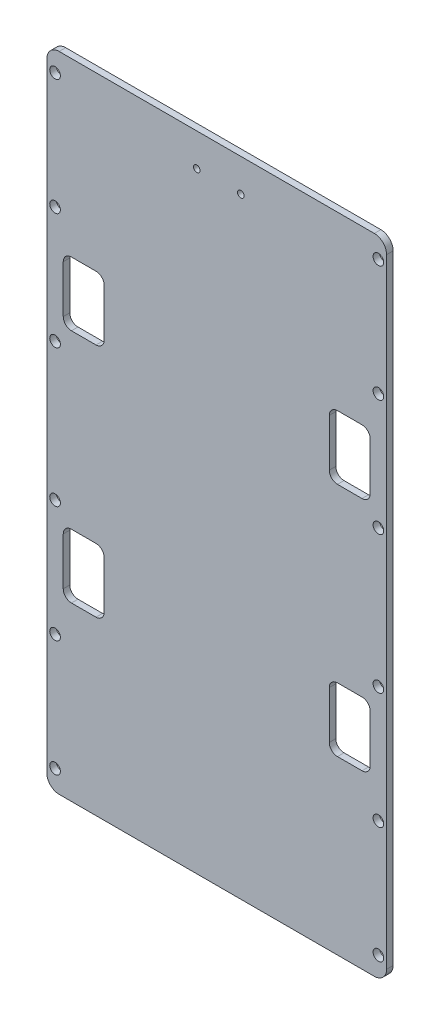
SolidWorks part; units mm, degrees
material "FR4_stuffedProtoboard"
ref_plane "Front Plane" through (0, 0, 0) normal (0, 0, 1) x (1, 0, 0)
ref_plane "Top Plane" through (0, 0, 0) normal (0, 1, 0) x (1, 0, 0)
ref_plane "Right Plane" through (0, 0, 0) normal (1, 0, 0) x (0, 0, -1)
sketch "Sketch1" plane through (0, 0, 0) normal (0, 0, 1) x (1, 0, 0)
  line L0 (-41.5, 0) -> (0, 0) construction
  line L1 (-38.5, 78.6) -> (38.5, 78.6)
  line L2 (-41.5, 75.6) -> (-41.5, -75.6)
  line L3 (-38.5, -78.6) -> (38.5, -78.6)
  line L4 (41.5, 75.6) -> (41.5, -75.6)
  line L5 (0, 0) -> (41.5, 0) construction
  line L7 (-34.5, 74.6) -> (-20.5, 74.6)
  line L8 (-37.5, 71.6) -> (-37.5, 52.1)
  line L9 (-35, 49.6) -> (-20.5, 49.6)
  line L10 (-17.5, 71.6) -> (-17.5, 52.6)
  line L11 (-12, 74.6) -> (13, 74.6)
  line L12 (-14.5, 72.1) -> (-14.5, 52.1)
  line L13 (-12, 49.6) -> (13, 49.6)
  line L14 (15.5, 72.1) -> (15.5, 52.1)
  line L15 (21, 74.6) -> (35, 74.6)
  line L16 (18.5, 72.1) -> (18.5, 52.1)
  line L17 (21, 49.6) -> (35, 49.6)
  line L18 (37.5, 72.1) -> (37.5, 52.1)
  line L19 (-35, 46.6) -> (-20, 46.6)
  line L20 (-37.5, 44.1) -> (-37.5, 21.1)
  line L21 (-35, 18.6) -> (-20, 18.6)
  line L22 (-17.5, 44.1) -> (-17.5, 21.1)
  line L23 (-12, 46.6) -> (13, 46.6)
  line L24 (-14.5, 44.1) -> (-14.5, 21.1)
  line L25 (-12, 18.6) -> (13, 18.6)
  line L26 (15.5, 44.1) -> (15.5, 21.1)
  line L27 (21, 46.6) -> (35, 46.6)
  line L28 (18.5, 44.1) -> (18.5, 21.1)
  line L29 (21, 18.6) -> (35, 18.6)
  line L30 (37.5, 44.1) -> (37.5, 21.1)
  line L31 (-35, 15.6) -> (-20, 15.6)
  line L32 (-37.5, 13.1) -> (-37.5, -13.1)
  line L33 (-35, -15.6) -> (-20, -15.6)
  line L34 (-17.5, 13.1) -> (-17.5, -13.1)
  line L35 (-12, 15.6) -> (13, 15.6)
  line L36 (-14.5, 13.1) -> (-14.5, -13.1)
  line L37 (-12, -15.6) -> (13, -15.6)
  line L38 (15.5, 13.1) -> (15.5, -13.1)
  line L39 (21, 15.6) -> (35, 15.6)
  line L40 (18.5, 13.1) -> (18.5, -13.1)
  line L41 (21, -15.6) -> (35, -15.6)
  line L42 (37.5, 13.1) -> (37.5, -13.1)
  line L43 (-35, -18.6) -> (-20, -18.6)
  line L44 (-37.5, -21.1) -> (-37.5, -44.1)
  line L45 (-35, -46.6) -> (-20, -46.6)
  line L46 (-17.5, -21.1) -> (-17.5, -44.1)
  line L47 (-12, -18.6) -> (13, -18.6)
  line L48 (-14.5, -21.1) -> (-14.5, -44.1)
  line L49 (-12, -46.6) -> (13, -46.6)
  line L50 (15.5, -21.1) -> (15.5, -44.1)
  line L51 (21, -18.6) -> (35, -18.6)
  line L52 (18.5, -21.1) -> (18.5, -44.1)
  line L53 (21, -46.6) -> (35, -46.6)
  line L54 (37.5, -21.1) -> (37.5, -44.1)
  line L55 (-35, -49.6) -> (-20, -49.6)
  line L56 (-37.5, -52.1) -> (-37.5, -72.1)
  line L57 (-35, -74.6) -> (-20, -74.6)
  line L58 (-17.5, -52.1) -> (-17.5, -72.1)
  line L59 (-12, -49.6) -> (13, -49.6)
  line L60 (-14.5, -52.1) -> (-14.5, -72.1)
  line L61 (-12, -74.6) -> (13, -74.6)
  line L62 (15.5, -52.1) -> (15.5, -72.1)
  line L63 (21, -49.6) -> (35, -49.6)
  line L64 (18.5, -52.1) -> (18.5, -72.1)
  line L65 (21, -74.6) -> (35, -74.6)
  line L66 (37.5, -52.1) -> (37.5, -72.1)
  arc A0 (-41.5, -75.6) -> (-38.5, -78.6) centre (-38.5, -75.6) ccw
  arc A1 (38.5, -78.6) -> (41.5, -75.6) centre (38.5, -75.6) ccw
  arc A2 (38.5, 78.6) -> (41.5, 75.6) centre (38.5, 75.6) cw
  arc A3 (-38.5, 78.6) -> (-41.5, 75.6) centre (-38.5, 75.6) ccw
  arc A4 (-20.5, 49.6) -> (-17.5, 52.6) centre (-20.5, 52.6) ccw
  arc A5 (-20.5, 74.6) -> (-17.5, 71.6) centre (-20.5, 71.6) cw
  arc A6 (-34.5, 74.6) -> (-37.5, 71.6) centre (-34.5, 71.6) ccw
  arc A7 (-20, -18.6) -> (-17.5, -21.1) centre (-20, -21.1) cw
  arc A8 (-35, -18.6) -> (-37.5, -21.1) centre (-35, -21.1) ccw
  arc A9 (-37.5, -44.1) -> (-35, -46.6) centre (-35, -44.1) ccw
  arc A10 (-20, -46.6) -> (-17.5, -44.1) centre (-20, -44.1) ccw
  arc A11 (-14.5, -44.1) -> (-12, -46.6) centre (-12, -44.1) ccw
  arc A12 (-12, -18.6) -> (-14.5, -21.1) centre (-12, -21.1) ccw
  arc A13 (13, -18.6) -> (15.5, -21.1) centre (13, -21.1) cw
  arc A14 (13, -46.6) -> (15.5, -44.1) centre (13, -44.1) ccw
  arc A15 (18.5, -44.1) -> (21, -46.6) centre (21, -44.1) ccw
  arc A16 (21, -18.6) -> (18.5, -21.1) centre (21, -21.1) ccw
  arc A17 (35, -18.6) -> (37.5, -21.1) centre (35, -21.1) cw
  arc A18 (35, -46.6) -> (37.5, -44.1) centre (35, -44.1) ccw
  arc A19 (35, -49.6) -> (37.5, -52.1) centre (35, -52.1) cw
  arc A20 (35, -74.6) -> (37.5, -72.1) centre (35, -72.1) ccw
  arc A21 (18.5, -72.1) -> (21, -74.6) centre (21, -72.1) ccw
  arc A22 (21, -49.6) -> (18.5, -52.1) centre (21, -52.1) ccw
  arc A23 (13, -49.6) -> (15.5, -52.1) centre (13, -52.1) cw
  arc A24 (13, -74.6) -> (15.5, -72.1) centre (13, -72.1) ccw
  arc A25 (-14.5, -72.1) -> (-12, -74.6) centre (-12, -72.1) ccw
  arc A26 (-12, -49.6) -> (-14.5, -52.1) centre (-12, -52.1) ccw
  arc A27 (-20, -49.6) -> (-17.5, -52.1) centre (-20, -52.1) cw
  arc A28 (-35, -49.6) -> (-37.5, -52.1) centre (-35, -52.1) ccw
  arc A29 (-37.5, -72.1) -> (-35, -74.6) centre (-35, -72.1) ccw
  arc A30 (-20, -74.6) -> (-17.5, -72.1) centre (-20, -72.1) ccw
  arc A31 (-37.5, -13.1) -> (-35, -15.6) centre (-35, -13.1) ccw
  arc A32 (-35, 15.6) -> (-37.5, 13.1) centre (-35, 13.1) ccw
  arc A33 (-20, 15.6) -> (-17.5, 13.1) centre (-20, 13.1) cw
  arc A34 (-20, -15.6) -> (-17.5, -13.1) centre (-20, -13.1) ccw
  arc A35 (-14.5, -13.1) -> (-12, -15.6) centre (-12, -13.1) ccw
  arc A36 (-12, 15.6) -> (-14.5, 13.1) centre (-12, 13.1) ccw
  arc A37 (13, 15.6) -> (15.5, 13.1) centre (13, 13.1) cw
  arc A38 (13, -15.6) -> (15.5, -13.1) centre (13, -13.1) ccw
  arc A39 (18.5, -13.1) -> (21, -15.6) centre (21, -13.1) ccw
  arc A40 (35, -15.6) -> (37.5, -13.1) centre (35, -13.1) ccw
  arc A41 (21, 15.6) -> (18.5, 13.1) centre (21, 13.1) ccw
  arc A42 (35, 15.6) -> (37.5, 13.1) centre (35, 13.1) cw
  arc A43 (35, 18.6) -> (37.5, 21.1) centre (35, 21.1) ccw
  arc A44 (18.5, 21.1) -> (21, 18.6) centre (21, 21.1) ccw
  arc A45 (21, 46.6) -> (18.5, 44.1) centre (21, 44.1) ccw
  arc A46 (35, 46.6) -> (37.5, 44.1) centre (35, 44.1) cw
  arc A47 (35, 49.6) -> (37.5, 52.1) centre (35, 52.1) ccw
  arc A48 (35, 74.6) -> (37.5, 72.1) centre (35, 72.1) cw
  arc A49 (18.5, 52.1) -> (21, 49.6) centre (21, 52.1) ccw
  arc A50 (21, 74.6) -> (18.5, 72.1) centre (21, 72.1) ccw
  arc A51 (13, 49.6) -> (15.5, 52.1) centre (13, 52.1) ccw
  arc A52 (13, 74.6) -> (15.5, 72.1) centre (13, 72.1) cw
  arc A53 (-12, 74.6) -> (-14.5, 72.1) centre (-12, 72.1) ccw
  arc A54 (-14.5, 52.1) -> (-12, 49.6) centre (-12, 52.1) ccw
  arc A55 (13, 18.6) -> (15.5, 21.1) centre (13, 21.1) ccw
  arc A56 (13, 46.6) -> (15.5, 44.1) centre (13, 44.1) cw
  arc A57 (-12, 46.6) -> (-14.5, 44.1) centre (-12, 44.1) ccw
  arc A58 (-14.5, 21.1) -> (-12, 18.6) centre (-12, 21.1) ccw
  arc A59 (-37.5, 21.1) -> (-35, 18.6) centre (-35, 21.1) ccw
  arc A60 (-20, 18.6) -> (-17.5, 21.1) centre (-20, 21.1) ccw
  arc A61 (-20, 46.6) -> (-17.5, 44.1) centre (-20, 44.1) cw
  arc A62 (-35, 46.6) -> (-37.5, 44.1) centre (-35, 44.1) ccw
  arc A63 (-37.5, 52.1) -> (-35, 49.6) centre (-35, 52.1) ccw
  point P72 (41.5, -78.6)
  point P75 (41.5, 78.6)
  point P78 (-41.5, 78.6)
  point P159 (37.5, 18.6)
  point P166 (37.5, 46.6)
  point P169 (37.5, 49.6)
  point P172 (37.5, 74.6)
  point P181 (15.5, 74.6)
  point P184 (-14.5, 74.6)
  dimension "D16" = 3
  dimension "D17" = 3
  dimension "D18" = 2.5
  dimension "D1" = 3
  dimension "D2" = 3
  dimension "D3" = 3
  dimension "D4" = 3
  dimension "D5" = 3
  dimension "D6" = 3
  dimension "D7" = 4
  dimension "D8" = 4
  dimension "D9" = 4
  dimension "D10" = 4
  dimension "D11" = 157.2
  dimension "D12" = 83
  dimension "D13" = 30
  dimension "D14" = 25
  dimension "D15" = 28
extrude "General Shape" add sketch "Sketch1" along normal blind 1.6 contours L8 A63 L9 A4 L10 A5 L7 A6 | L12 A54 L13 A51 L14 A52 L11 A53 | L15 A50 L16 A49 L17 A47 L18 A48 | L1 A3 L2 A0 L3 A1 L4 A2 A63 L8 A6 L7 A5 L10 A4 L9 A62 L19 A61 L22 A60 L21 A59 L20 A58 L24 A57 L23 A56 L26 A55 L25 A54 L12 A53 L11 A52 L14 A51 L13 A50 L15 A48 L18 A47 L17 | L24 A58 L25 A55 L26 A56 L23 A57 | L19 A62 L20 A59 L21 A60 L22 A61 | A46 L27 A45 L28 A44 L29 A43 L30 | A42 L39 A41 L40 A39 L41 A40 L42 | L37 A38 L38 A37 L35 A36 L36 A35 | L33 A34 L34 A33 L31 A32 L32 A31 | L45 A10 L46 A7 L43 A8 L44 A9 | L49 A14 L50 A13 L47 A12 L48 A11 | L53 A18 L54 A17 L51 A16 L52 A15 | L63 A22 L64 A21 L65 A20 L66 A19 | L59 A26 L60 A25 L61 A24 L62 A23 | L57 A30 L58 A27 L55 A28 L56 A29
sketch "Sketch2" plane through (0, 0, 0) normal (0, 0, -1) x (-1, 0, 0)
  line L0 (38.5, 78.6) -> (-38.5, 78.6) construction
  line L1 (-22, 64) -> (0, 64) construction
  line L2 (-41.5, 75.6) -> (-41.5, -75.6) construction
  line L3 (-22, 64) -> (-22, 54) construction
  line L4 (-22, -71.6) -> (0, -71.6) construction
  line L5 (-22, -71.6) -> (-22, -61.6) construction
  line L7 (38.5, -78.6) -> (-38.5, -78.6) construction
  line L8 (-41.5, 75.6) -> (-41.5, -75.6) construction
  circle A0 centre (-22, 64) radius 1.2
  circle A1 centre (0, 64) radius 1.2
  circle A2 centre (22, 64) radius 1.2
  circle A3 centre (0, 54) radius 1.2
  circle A4 centre (22, 54) radius 1.2
  circle A5 centre (0, 44) radius 1.2
  circle A6 centre (22, 44) radius 1.2
  circle A7 centre (0, 34) radius 1.2
  circle A8 centre (22, 34) radius 1.2
  circle A9 centre (0, 24) radius 1.2
  circle A10 centre (22, 24) radius 1.2
  circle A11 centre (-22, 54) radius 1.2
  circle A12 centre (-22, 44) radius 1.2
  circle A13 centre (-22, 34) radius 1.2
  circle A14 centre (-22, 24) radius 1.2
  circle A15 centre (-22, -71.6) radius 1.2
  circle A16 centre (0, -71.6) radius 1.2
  circle A17 centre (22, -71.6) radius 1.2
  circle A18 centre (0, -61.6) radius 1.2
  circle A19 centre (22, -61.6) radius 1.2
  circle A20 centre (0, -51.6) radius 1.2
  circle A21 centre (22, -51.6) radius 1.2
  circle A22 centre (0, -41.6) radius 1.2
  circle A23 centre (22, -41.6) radius 1.2
  circle A24 centre (0, -31.6) radius 1.2
  circle A25 centre (22, -31.6) radius 1.2
  circle A26 centre (0, -21.6) radius 1.2
  circle A27 centre (22, -21.6) radius 1.2
  circle A28 centre (-22, -61.6) radius 1.2
  circle A29 centre (-22, -51.6) radius 1.2
  circle A30 centre (-22, -41.6) radius 1.2
  circle A31 centre (-22, -31.6) radius 1.2
  circle A32 centre (-22, -21.6) radius 1.2
  dimension "D3" = 2.4
  dimension "D9" = 2.4
  dimension "D1" = 14.6
  dimension "D2" = 19.5
  dimension "D6" = 90
  dimension "D7" = 22
  dimension "D8" = 10
  dimension "D10" = 7
  dimension "D11" = 19.5
  dimension "D14" = 90
  dimension "D15" = 22
  dimension "D16" = 10
  dimension "D4" = 3
  dimension "D5" = 5
  dimension "D12" = 3
  dimension "D13" = 6
hole_wizard "M2 Clearance Hole1" positions "3DSketch1" profile "Sketch4" hole size "M2" standard "ANSI Metric" end condition up to next
sketch3d "3DSketch1"
  line L0 (-39.5, 73.6, 0) -> (-39.5, 45.2, 0) construction
  line L1 (-39.5, 45.2, 0) -> (-39.5, 16.8, 0) construction
  line L3 (-41.5, 75.6, 0) -> (-41.5, -75.6, 0) construction
  line L4 (-38.5, 78.6, 0) -> (38.5, 78.6, 0) construction
  point P0 (-39.5, 73.6, 0)
  point P2 (-39.5, 45.2, 0)
  point P4 (-39.5, 16.8, 0)
  dimension "D1" = 2
  dimension "D2" = 5
  dimension "D3" = 28.4
sketch "Sketch4" plane through (-39.5, 73.6, 0) normal (1, 0, 0) x (0, 1, 0)
  line L0 (0, 0) -> (0, 1.6)
  line L1 (0, 1.6) -> (1.3, 1.6)
  line L2 (1.3, 1.6) -> (1.3, 0)
  line L5 (1.3, 0) -> (0, 0)
  line L11 (0, -6.35) -> (0, 107.95) construction
  dimension "Thru Hole Dia." = 2.6
  dimension "Thru Hole Depth" = 1.6
mirror "Mirror1" about plane through (0, 0, 0) normal (1, 0, 0) of "M2 Clearance Hole1"
mirror "Mirror2" about plane through (0, 0, 0) normal (0, 1, 0) of "Mirror1", "M2 Clearance Hole1"
sketch "Sketch5" plane through (0, 0, 0) normal (0, 0, -1) x (-1, 0, 0)
  line L0 (12, 74.6) -> (-13, 74.6) construction
  line L1 (-5.5, 73.6) -> (4.5, 73.6)
  line L2 (-8, 71.1) -> (-8, 70.1)
  line L3 (-5.5, 67.6) -> (4.5, 67.6)
  line L4 (7, 71.1) -> (7, 70.1)
  line L5 (14.5, 72.1) -> (14.5, 52.1) construction
  line L6 (-7.5, 68.6) -> (6.5, 68.6)
  arc A0 (4.5, 73.6) -> (7, 71.1) centre (4.5, 71.1) cw
  arc A1 (4.5, 67.6) -> (7, 70.1) centre (4.5, 70.1) ccw
  arc A2 (-8, 70.1) -> (-5.5, 67.6) centre (-5.5, 70.1) ccw
  arc A3 (-5.5, 73.6) -> (-8, 71.1) centre (-5.5, 71.1) ccw
  circle A4 centre (-5.88, 70.6) radius 0.8
  circle A5 centre (4.88, 70.6) radius 0.8
  point P6 (7, 73.6)
  point P9 (7, 67.6)
  point P14 (-8, 73.6)
  dimension "D3" = 2.5
  dimension "D5" = 1.6
  dimension "D6" = 2.12
  dimension "D1" = 6
  dimension "D2" = 15
  dimension "D4" = 1
  dimension "D7" = 2.12
  dimension "D8" = 7.5
  dimension "D9" = 3
  dimension "D10" = 3
  dimension "D11" = 14
extrude "Connector holes" cut sketch "Sketch5" against normal through all contours A4 | A5
sketch "Sketch6" plane through (0, 0, 0) normal (0, 0, -1) x (-1, 0, 0)
  line L0 (38.5, -78.6) -> (-38.5, -78.6) construction
  line L1 (-35.5, 36.6) -> (-29.5, 36.6)
  line L2 (-37.5, 34.6) -> (-37.5, 23)
  line L3 (-35.5, 21) -> (-29.5, 21)
  line L4 (-27.5, 34.6) -> (-27.5, 23)
  line L5 (29.5, 36.6) -> (35.5, 36.6)
  line L6 (27.5, 34.6) -> (27.5, 23)
  line L7 (29.5, 21) -> (35.5, 21)
  line L8 (37.5, 34.6) -> (37.5, 23)
  line L9 (-35.5, -21) -> (-29.5, -21)
  line L10 (-37.5, -23) -> (-37.5, -34.6)
  line L11 (-35.5, -36.6) -> (-29.5, -36.6)
  line L12 (-27.5, -23) -> (-27.5, -34.6)
  line L13 (29.5, -21) -> (35.5, -21)
  line L14 (27.5, -23) -> (27.5, -34.6)
  line L15 (29.5, -36.6) -> (35.5, -36.6)
  line L16 (37.5, -23) -> (37.5, -34.6)
  line L17 (38.5, 78.6) -> (-38.5, 78.6) construction
  line L18 (-41.5, 75.6) -> (-41.5, -75.6) construction
  line L19 (41.5, 75.6) -> (41.5, -75.6) construction
  arc A0 (-37.5, 23) -> (-35.5, 21) centre (-35.5, 23) ccw
  arc A1 (-29.5, 21) -> (-27.5, 23) centre (-29.5, 23) ccw
  arc A2 (-29.5, 36.6) -> (-27.5, 34.6) centre (-29.5, 34.6) cw
  arc A3 (-35.5, 36.6) -> (-37.5, 34.6) centre (-35.5, 34.6) ccw
  arc A4 (-37.5, -34.6) -> (-35.5, -36.6) centre (-35.5, -34.6) ccw
  arc A5 (-29.5, -36.6) -> (-27.5, -34.6) centre (-29.5, -34.6) ccw
  arc A6 (-29.5, -21) -> (-27.5, -23) centre (-29.5, -23) cw
  arc A7 (-35.5, -21) -> (-37.5, -23) centre (-35.5, -23) ccw
  arc A8 (27.5, -34.6) -> (29.5, -36.6) centre (29.5, -34.6) ccw
  arc A9 (35.5, -21) -> (37.5, -23) centre (35.5, -23) cw
  arc A10 (29.5, -21) -> (27.5, -23) centre (29.5, -23) ccw
  arc A11 (35.5, -36.6) -> (37.5, -34.6) centre (35.5, -34.6) ccw
  arc A12 (35.5, 21) -> (37.5, 23) centre (35.5, 23) ccw
  arc A13 (35.5, 36.6) -> (37.5, 34.6) centre (35.5, 34.6) cw
  arc A14 (29.5, 36.6) -> (27.5, 34.6) centre (29.5, 34.6) ccw
  arc A15 (27.5, 23) -> (29.5, 21) centre (29.5, 23) ccw
  point P16 (-24.0152, 38.5086)
  point P17 (-35, 26.6982)
  point P18 (35.1331, 38.3691)
  point P19 (27.3351, 29.6614)
  point P20 (35.428, 38.529)
  point P21 (26.5376, 25.8502)
  point P22 (27.0727, 24.8046)
  point P23 (-22, -28.8892)
  point P24 (-26.0058, -21.6)
  dimension "D7" = 2
  dimension "D8" = 2
  dimension "D9" = 2
  dimension "D10" = 2
  dimension "D11" = 2
  dimension "D1" = 42
  dimension "D2" = 42
  dimension "D3" = 4
  dimension "D4" = 10
  dimension "D5" = 4
  dimension "D6" = 42
extrude "Star Tracker Cutouts" cut sketch "Sketch6" against normal through all
